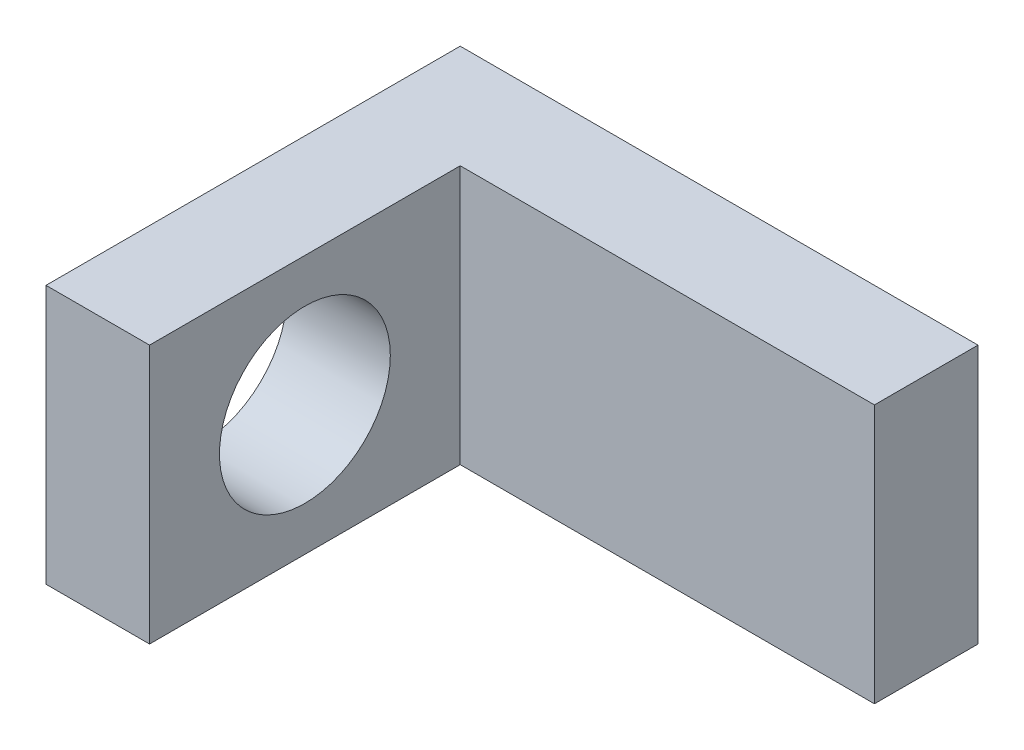
SolidWorks part; units mm, degrees
ref_plane "Front Plane" through (0, 0, 0) normal (0, 0, 1) x (1, 0, 0)
ref_plane "Top Plane" through (0, 0, 0) normal (0, 1, 0) x (1, 0, 0)
ref_plane "Right Plane" through (0, 0, 0) normal (1, 0, 0) x (0, 0, -1)
sketch "Sketch1" plane through (0, 0, 0) normal (0, 1, 0) x (1, 0, 0)
  line L0 (0, 0) -> (0, -8)
  line L1 (0, -8) -> (2, -8)
  line L2 (2, -8) -> (2, -2)
  line L3 (2, -2) -> (10, -2)
  line L4 (10, -2) -> (10, 0)
  line L5 (10, 0) -> (0, 0)
  dimension "D1" = 10
  dimension "D2" = 2
  dimension "D3" = 2
  dimension "D4" = 8
extrude "Boss-Extrude1" add sketch "Sketch1" along normal blind 5
hole_wizard "Tap Drill for M4x0.7 Tap1" positions "Sketch6" profile "Sketch5" hole size "M4x0.7" standard "ANSI Metric" end condition through all
sketch "Sketch6" plane through (2, 0, 0) normal (1, 0, 0) x (0, 0, -1)
  line L0 (-8, 5) -> (-5, 5) construction
  line L1 (-8, 5) -> (-2, 5) construction
  line L2 (-5, 5) -> (-5, 2.5023) construction
  point P0 (-5, 2.5023)
  dimension "D1" = 3
  dimension "D2" = 2.4977
sketch "Sketch5" plane through (2, 2.5023, 5) normal (0, 1, 0) x (0, 0, -1)
  line L0 (0, 0) -> (0, 2)
  line L1 (0, 2) -> (1.65, 2)
  line L2 (1.65, 2) -> (1.65, 0)
  line L5 (1.65, 0) -> (0, 0)
  line L11 (0, -6.35) -> (0, 107.95) construction
  dimension "Thru Hole Dia." = 3.3
  dimension "Thru Hole Depth" = 2
